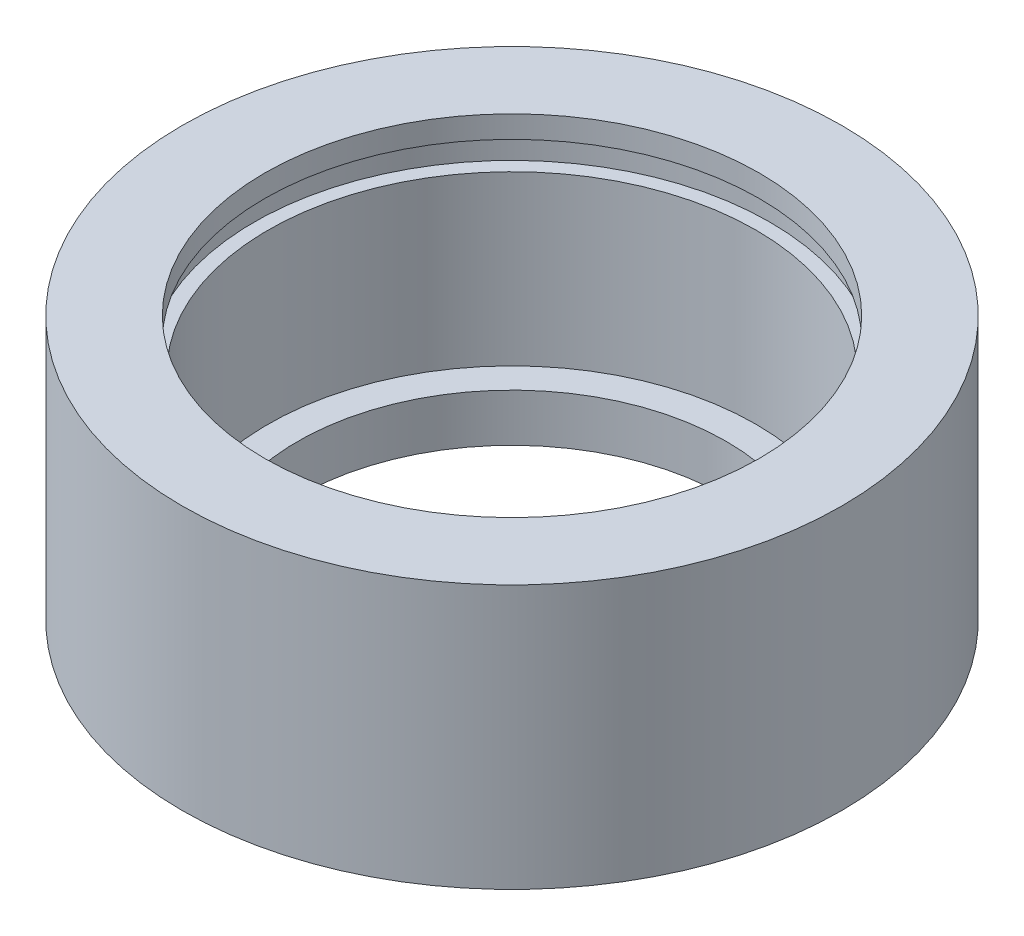
SolidWorks part; units mm, degrees
material "AISI 4130 Steel, annealed at 865C"
ref_plane "Front Plane" through (0, 0, 0) normal (0, 0, 1) x (1, 0, 0)
ref_plane "Top Plane" through (0, 0, 0) normal (0, 1, 0) x (1, 0, 0)
ref_plane "Right Plane" through (0, 0, 0) normal (1, 0, 0) x (0, 0, -1)
sketch "Sketch1" plane through (0, 0, 0) normal (0, 0, 1) x (1, 0, 0)
  line L0 (0, 0) -> (0, 8.0572) construction
  line L1 (-12.7, -5.08) -> (-8.255, -5.08)
  line L2 (-8.255, -5.08) -> (-8.255, -3.2385)
  line L3 (-8.255, -3.2385) -> (-9.398, -3.2385)
  line L4 (-9.398, -3.2385) -> (-9.398, 3.2385)
  line L5 (-9.398, 3.2385) -> (-9.9314, 3.2385)
  line L6 (-9.9314, 3.2385) -> (-9.9314, 4.2291)
  line L7 (-9.9314, 4.2291) -> (-9.525, 4.2291)
  line L8 (-9.525, 4.2291) -> (-9.525, 5.08)
  line L9 (-9.525, 5.08) -> (-12.7, 5.08)
  line L10 (-12.7, 5.08) -> (-12.7, -5.08)
  point P5 (-9.6647, 3.2385)
  dimension "D1" = 19.05
  dimension "D2" = 10.16
  dimension "D3" = 0.9906
  dimension "D4" = 6.477
  dimension "D5" = 16.51
  dimension "D6" = 18.796
  dimension "D7" = 19.8628
  dimension "D8" = 1.8415
  dimension "D9" = 25.4
  dimension "D10" = 5.08
revolve "Revolve1" add sketch "Sketch1" angle 360 about L0
